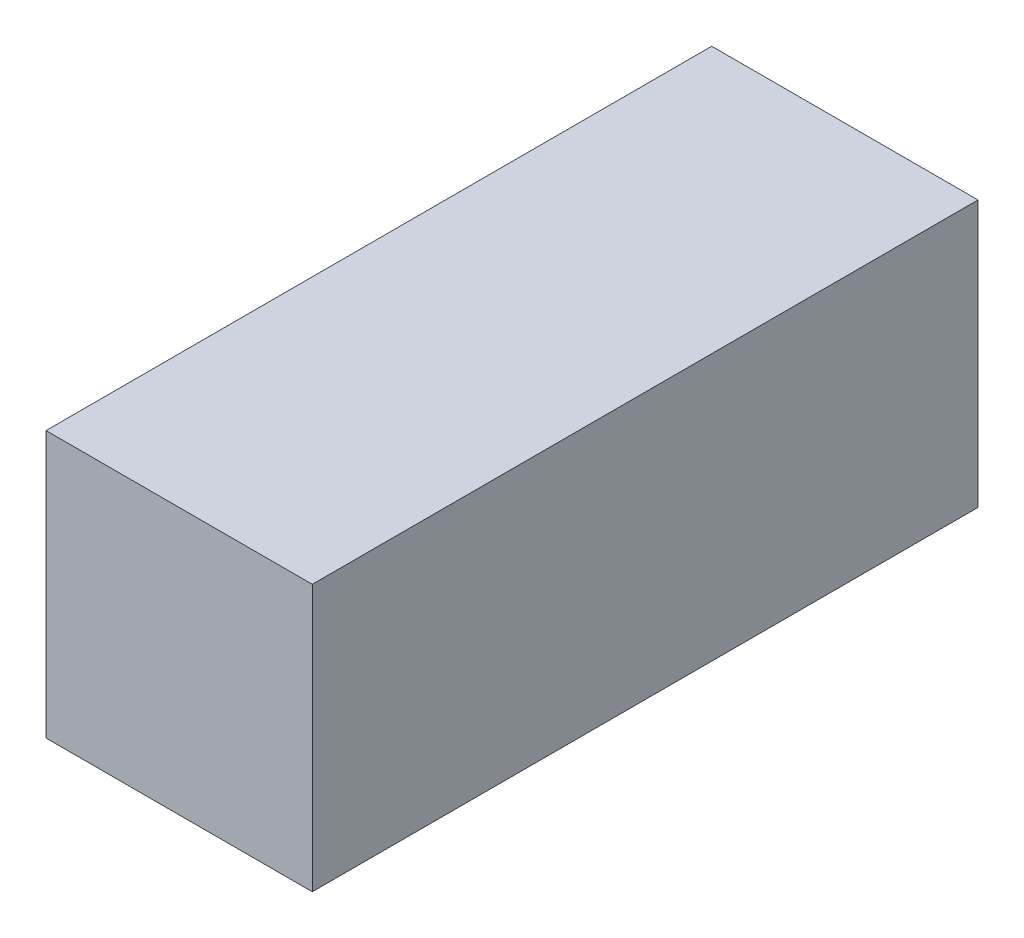
SolidWorks part; units mm, degrees
ref_plane "Front Plane" through (0, 0, 0) normal (0, 0, 1) x (1, 0, 0)
ref_plane "Top Plane" through (0, 0, 0) normal (0, 1, 0) x (1, 0, 0)
ref_plane "Right Plane" through (0, 0, 0) normal (1, 0, 0) x (0, 0, -1)
sketch "Sketch1" plane through (0, 0, 0) normal (0, 0, 1) x (1, 0, 0)
  line L1 (-25.4, -25.4) -> (25.4, -25.4)
  line L2 (-25.4, -25.4) -> (-25.4, 25.4)
  line L3 (-25.4, 25.4) -> (25.4, 25.4)
  line L4 (25.4, -25.4) -> (25.4, 25.4)
  line L5 (-25.4, -25.4) -> (25.4, 25.4) construction
  line L6 (-25.4, 25.4) -> (25.4, -25.4) construction
  point P0 (0, 0)
  dimension "D1" = 50.8
  dimension "D2" = 50.8
extrude "Boss-Extrude1" add sketch "Sketch1" along normal blind 127
